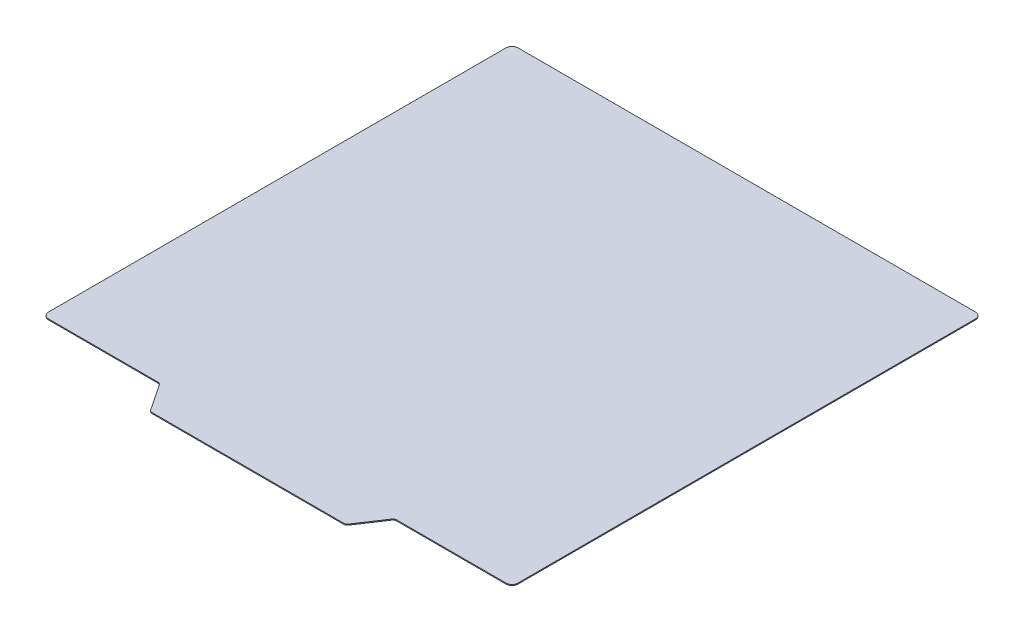
SolidWorks part; units mm, degrees
ref_plane "Ebene vorne" through (0, 0, 0) normal (0, 0, 1) x (1, 0, 0)
ref_plane "Ebene oben" through (0, 0, 0) normal (0, 1, 0) x (1, 0, 0)
ref_plane "Ebene rechts" through (0, 0, 0) normal (1, 0, 0) x (0, 0, -1)
sketch "Skizze1" plane through (0, 0, 0) normal (0, 1, 0) x (1, 0, 0)
  line L0 (-117, -120) -> (117, -120)
  line L1 (120, -117) -> (120, 117)
  line L2 (117, 120) -> (-117, 120)
  line L3 (-120, 117) -> (-120, -117)
  line L4 (0, 120) -> (0, -120) construction
  line L5 (-120, 0) -> (120, 0) construction
  arc A0 (-120, -117) -> (-117, -120) centre (-117, -117) ccw
  arc A1 (117, -120) -> (120, -117) centre (117, -117) ccw
  arc A2 (120, 117) -> (117, 120) centre (117, 117) ccw
  arc A3 (-117, 120) -> (-120, 117) centre (-117, 117) ccw
  dimension "D2" = 3
  dimension "D1" = 240
extrude "Aufsatz-Linear austragen1" add sketch "Skizze1" along normal blind 0.5
sketch "Sketch1" plane through (0, 0.5, 0) normal (0, 1, 0) x (1, 0, 0)
  line L0 (-60, -120) -> (-50, -135)
  line L1 (-117, -120) -> (117, -120) construction
  line L2 (-50, -135) -> (50, -135)
  line L3 (0, -135) -> (0, -120) construction
  line L4 (60, -120) -> (-60, -120)
  line L5 (60, -120) -> (50, -135)
  dimension "D1" = 15
  dimension "D2" = 100
  dimension "D3" = 120
extrude "Boss-Extrude1" add sketch "Sketch1" against normal up to surface (0.5 mm away) up to face at (0, 0, 0)
fillet "Fillet1" radius 2 4 edges at (-50, 0.25, 135) (-60, 0.25, 120) (50, 0.25, 135) (60, 0.25, 120)
